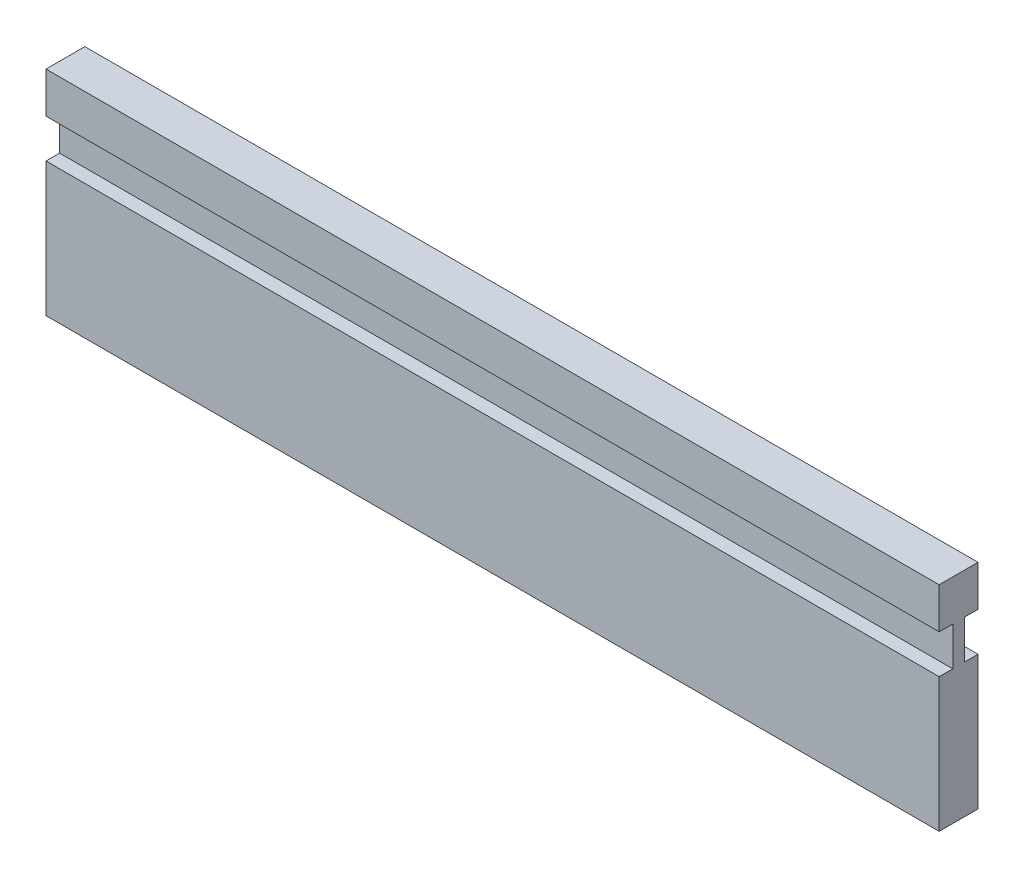
SolidWorks part; units mm, degrees
ref_plane "Alzado" through (0, 0, 0) normal (0, 0, 1) x (1, 0, 0)
ref_plane "Planta" through (0, 0, 0) normal (0, 1, 0) x (1, 0, 0)
ref_plane "Vista lateral" through (0, 0, 0) normal (1, 0, 0) x (0, 0, -1)
sketch "Croquis1" plane through (0, 0, 0) normal (0, 0, 1) x (1, 0, 0)
  line L1 (230, -55) -> (-230, -55)
  line L2 (230, -55) -> (230, 55)
  line L3 (230, 55) -> (-230, 55)
  line L4 (-230, -55) -> (-230, 55)
  line L5 (230, -55) -> (-230, 55) construction
  line L6 (230, 55) -> (-230, -55) construction
  point P0 (0, 0)
  dimension "D1" = 460
  dimension "D2" = 110
extrude "Saliente-Extruir1" add sketch "Croquis1" along normal blind 20
sketch "Croquis8" plane through (0, 0, 20) normal (0, 0, 1) x (1, 0, 0)
  line L0 (230, -55) -> (230, 55) construction
  line L1 (-250, 34) -> (230, 34)
  line L2 (-250, 34) -> (-250, 14)
  line L3 (-250, 14) -> (230, 14)
  line L4 (230, 34) -> (230, 14)
  line L5 (-250, 34) -> (230, 14) construction
  line L6 (-250, 14) -> (230, 34) construction
  line L7 (230, 55) -> (-230, 55) construction
  point P0 (-10, 24)
  dimension "D1" = 21
  dimension "D2" = 20
  dimension "D3" = 480
extrude "Cortar-Extruir3" cut sketch "Croquis8" against normal blind 7
sketch "Croquis9" plane through (0, 0, 0) normal (0, 0, -1) x (-1, 0, 0)
  line L0 (230, 55) -> (230, -55) construction
  line L1 (-240, 34) -> (230, 34)
  line L2 (-240, 34) -> (-240, 14)
  line L3 (-240, 14) -> (230, 14)
  line L4 (230, 34) -> (230, 14)
  line L5 (-240, 34) -> (230, 14) construction
  line L6 (-240, 14) -> (230, 34) construction
  line L7 (-230, 55) -> (230, 55) construction
  point P0 (-5, 24)
  dimension "D1" = 21
  dimension "D2" = 20
extrude "Cortar-Extruir4" cut sketch "Croquis9" against normal blind 7
